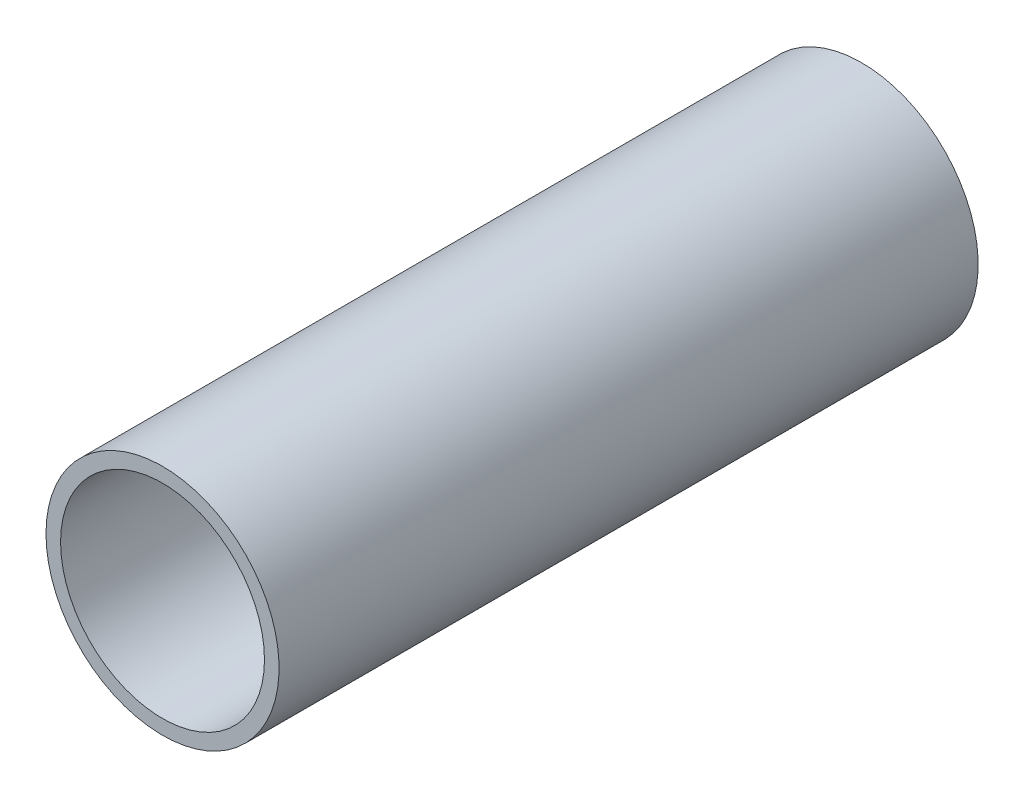
SolidWorks part; units mm, degrees
ref_plane "Front Plane" through (0, 0, 0) normal (0, 0, 1) x (1, 0, 0)
ref_plane "Top Plane" through (0, 0, 0) normal (0, 1, 0) x (1, 0, 0)
ref_plane "Right Plane" through (0, 0, 0) normal (1, 0, 0) x (0, 0, -1)
sketch "Sketch1" plane through (0, 0, 0) normal (0, 0, 1) x (1, 0, 0)
  line L0 (-50.8, 0) -> (50.8, 0) construction
  line L1 (0, -50.8) -> (0, 50.8) construction
  circle A0 centre (0, 0) radius 50.8
  circle A1 centre (0, 0) radius 44.45
  point P4 (0, 0)
  point P9 (0, 0)
  point P10 (44.45, 0)
  dimension "D1" = 88.9
  dimension "OD" = 101.6
  dimension "Wall Thickness" = 6.35
sketch "Sketch2" plane through (0, 0, 0) normal (1, 0, 0) x (0, 0, -1)
  line L0 (152.4, 50.8) -> (-152.4, 50.8) construction
  line L1 (0, 50.8) -> (0, -50.8) construction
  point P3 (-35.56, 50.8)
  point P4 (0, 50.8)
  point P5 (35.56, 50.8)
  dimension "D1" = 116.84
  dimension "D2" = 116.84
  dimension "Length" = 304.8
sketch "Sketch3" plane through (0, 0, 0) normal (0, 0, 1) x (1, 0, 0)
  line L0 (0, -50.8) -> (0, 50.8) construction
  circle A0 centre (0, 0) radius 50.8
  circle A1 centre (0, 0) radius 44.45
  circle A2 centre (0, 0) radius 44.45 construction
extrude "Boss-Extrude1" add sketch "Sketch3" along normal mid plane 304.8
equation "\"D1@Boss-Extrude1\" = \"Length@Sketch2\""
equation "\"D1@Sketch2\"=\"OD@Sketch1\"*1.15"
equation "\"D2@Sketch2\"=\"D1@Sketch2\""
